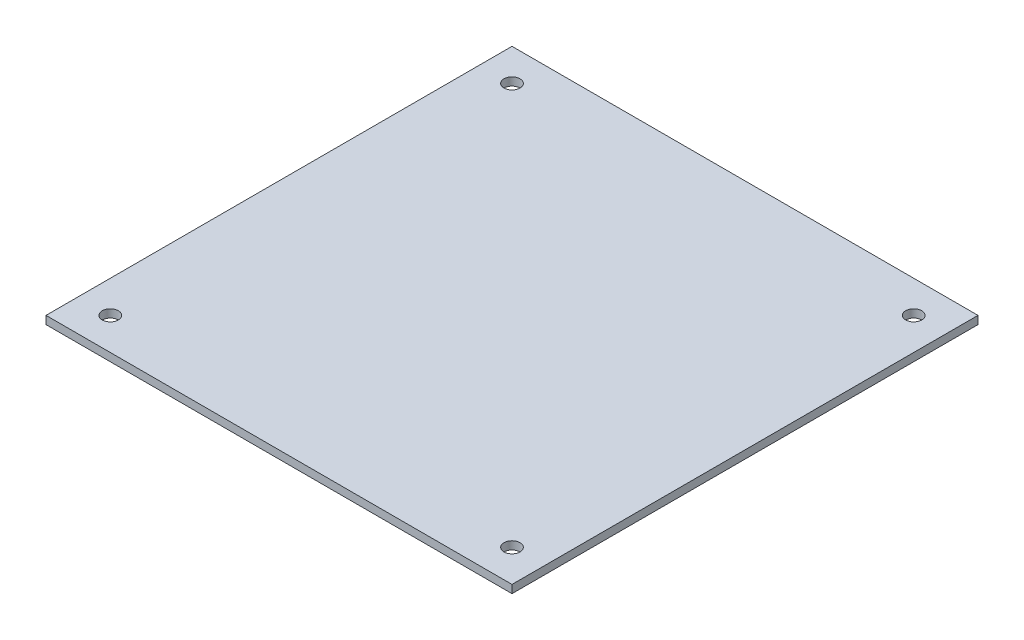
SolidWorks part; units mm, degrees
material "Polyetheretherketone (PEEK)"
ref_plane "Front" through (0, 0, 0) normal (0, 0, 1) x (1, 0, 0)
ref_plane "Top" through (0, 0, 0) normal (0, 1, 0) x (1, 0, 0)
ref_plane "Right" through (0, 0, 0) normal (1, 0, 0) x (0, 0, -1)
sketch "Sketch1" plane through (0, 0, 0) normal (0, 1, 0) x (1, 0, 0)
  line L0 (-44.5813, 0) -> (72.2872, 0) construction
  line L1 (-72.5, 72.5) -> (72.5, 72.5)
  line L2 (-72.5, 72.5) -> (-72.5, -72.5)
  line L3 (-72.5, -72.5) -> (72.5, -72.5)
  line L4 (72.5, 72.5) -> (72.5, -72.5)
  line L5 (0, 51.2559) -> (0, -64.1014) construction
  circle A0 centre (-62.5, 62.5) radius 2.5
  circle A1 centre (62.5, 62.5) radius 2.5
  circle A2 centre (62.5, -62.5) radius 2.5
  circle A3 centre (-62.5, -62.5) radius 2.5
  point P20 (0, 0)
  dimension "D3" = 4
  dimension "D4" = 5
  dimension "D5" = 62.5
  dimension "D6" = 62.5
  dimension "D1" = 145
  dimension "D2" = 145
extrude "Boss-Extrude1" add sketch "Sketch1" along normal blind 2.5
